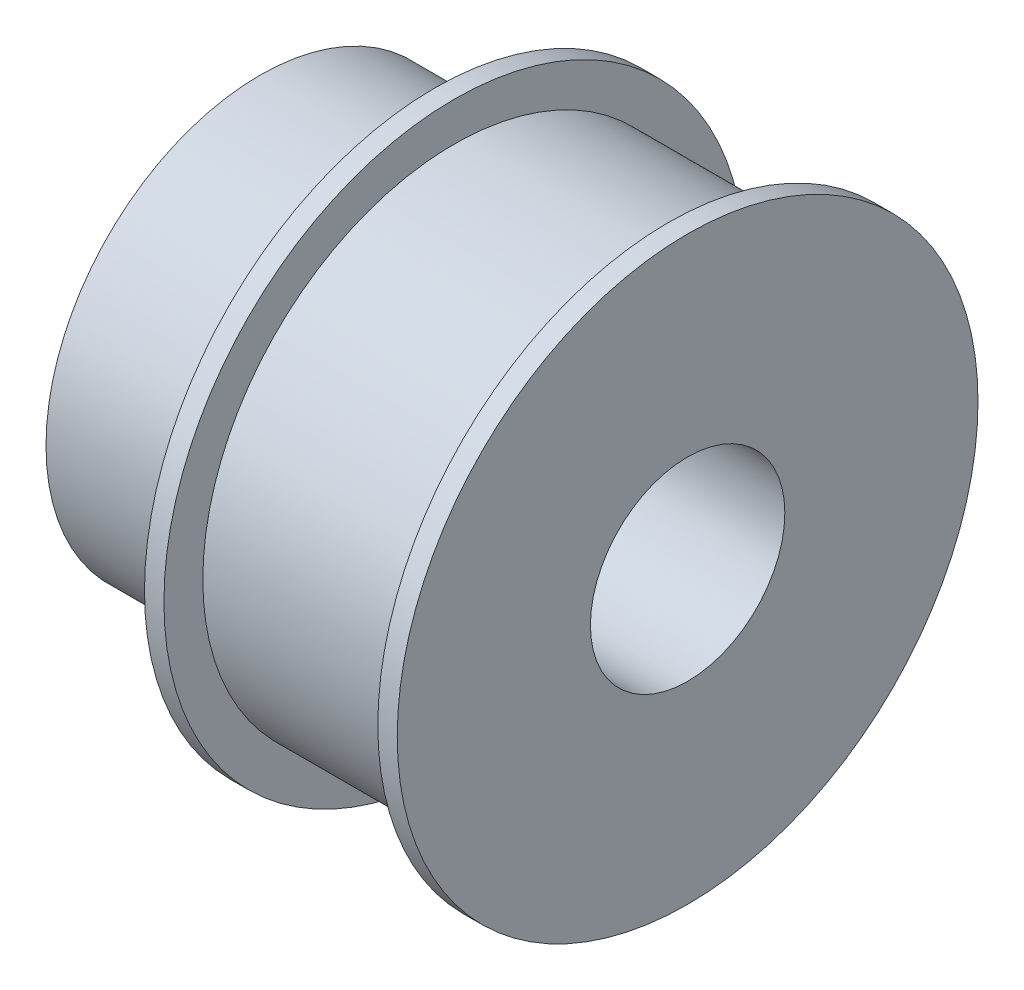
SolidWorks part; units mm, degrees
ref_plane "前视基准面" through (0, 0, 0) normal (0, 0, 1) x (1, 0, 0)
ref_plane "上视基准面" through (0, 0, 0) normal (0, 1, 0) x (1, 0, 0)
ref_plane "右视基准面" through (0, 0, 0) normal (1, 0, 0) x (0, 0, -1)
sketch "草图1" plane through (0, 0, 0) normal (1, 0, 0) x (0, 0, -1)
  circle A0 centre (0, 0) radius 12.935
  dimension "D1" = 25.87
extrude "凸台-拉伸1" add sketch "草图1" along normal blind 11
sketch "草图2" plane through (11, 0, 0) normal (1, 0, 0) x (0, 0, -1)
  circle A1 centre (0, 0) radius 14.935
  circle A2 centre (0, 0) radius 12.935 construction
  dimension "D1" = 2
extrude "凸台-拉伸2" add sketch "草图2" along normal blind 1
sketch "草图3" plane through (0, 0, 0) normal (-1, 0, 0) x (0, 0, 1)
  circle A0 centre (0, 0) radius 14.935
extrude "凸台-拉伸3" add sketch "草图3" along normal blind 1
sketch "草图4" plane through (-1, 0, 0) normal (-1, 0, 0) x (0, 0, 1)
  circle A0 centre (0, 0) radius 11
  dimension "D1" = 22
extrude "凸台-拉伸4" add sketch "草图4" along normal offset from surface (9 mm away) 22 up to face at (12, 0, -14.935)
sketch "草图5" plane through (-10, 0, 0) normal (-1, 0, 0) x (0, 0, 1)
  circle A0 centre (0, 0) radius 5
  dimension "D1" = 10
extrude "切除-拉伸1" cut sketch "草图5" against normal blind 30
